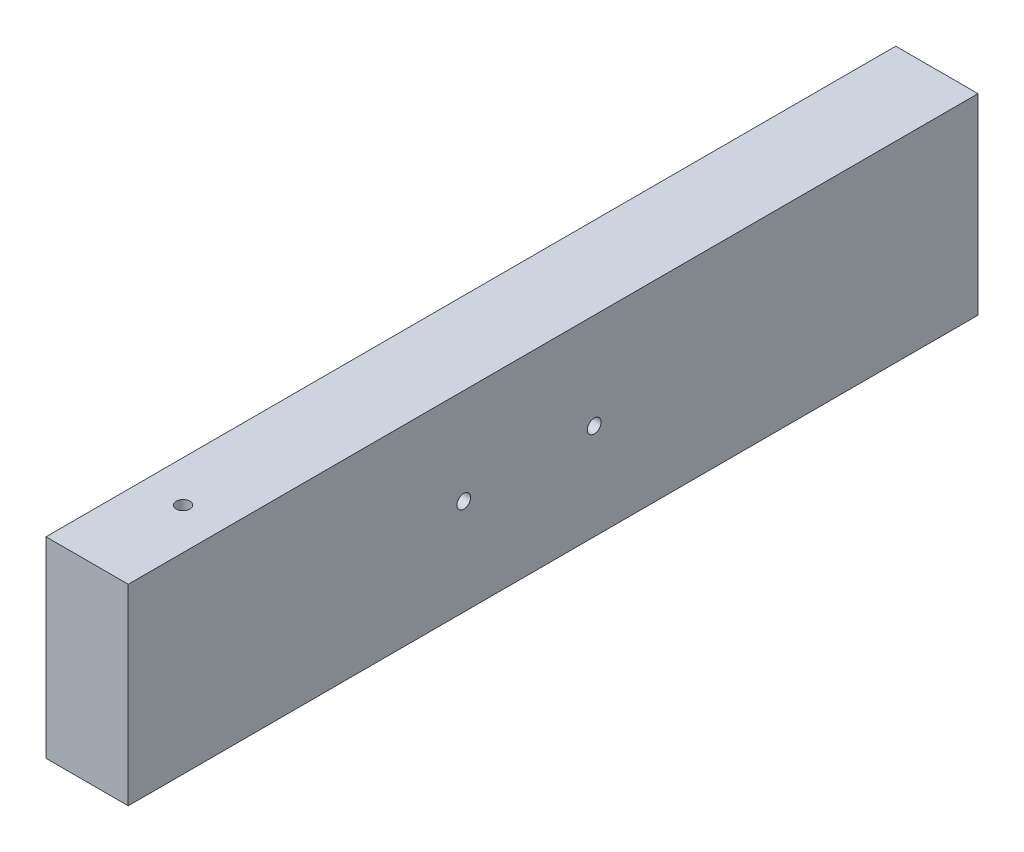
SolidWorks part; units mm, degrees
material "1060 Alloy"
ref_plane "Front Plane" through (0, 0, 0) normal (0, 0, 1) x (1, 0, 0)
ref_plane "Top Plane" through (0, 0, 0) normal (0, 1, 0) x (1, 0, 0)
ref_plane "Right Plane" through (0, 0, 0) normal (1, 0, 0) x (0, 0, -1)
sketch "Sketch1" plane through (0, 0, 0) normal (0, 1, 0) x (1, 0, 0)
  line L1 (-144.8803, -70.9153) -> (-106.7803, -70.9153)
  line L2 (-144.8803, -70.9153) -> (-144.8803, 322.7847)
  line L3 (-144.8803, 322.7847) -> (-106.7803, 322.7847)
  line L4 (-106.7803, -70.9153) -> (-106.7803, 322.7847)
  line L5 (-144.8803, -70.9153) -> (-106.7803, 322.7847) construction
  line L6 (-144.8803, 322.7847) -> (-106.7803, -70.9153) construction
  point P0 (-125.8303, 125.9347)
  dimension "D1" = 393.7
  dimension "D2" = 38.1
extrude "Boss-Extrude1" add sketch "Sketch1" along normal blind 88.9
sketch "Sketch2" plane through (0, 0, 0) normal (0, -1, 0) x (-1, 0, 0)
  line L0 (144.8803, -70.9153) -> (106.7803, -70.9153) construction
  line L1 (144.8803, 322.7847) -> (144.8803, -70.9153) construction
  circle A0 centre (125.8303, -26.4653) radius 3.175
  dimension "D1" = 6.35
  dimension "D2" = 44.45
  dimension "D3" = 19.05
sketch "Sketch3" plane through (-144.8803, 0, 0) normal (-1, 0, 0) x (0, 0, 1)
  line L0 (-322.7847, 88.9) -> (-322.7847, 0) construction
  line L1 (-322.7847, 88.9) -> (-322.7847, 0) construction
  line L2 (-322.7847, 0) -> (70.9153, 0) construction
  line L3 (70.9153, 88.9) -> (-322.7847, 88.9) construction
  circle A0 centre (-84.5327, 44.45) radius 3.175
  circle A1 centre (-144.9847, 44.45) radius 3.175
  dimension "D1" = 6.35
  dimension "D2" = 238.252
  dimension "D3" = 44.45
  dimension "D4" = 6.35
  dimension "D5" = 177.8
  dimension "D6" = 44.45
extrude "Cut-Extrude2" cut sketch "Sketch3" against normal through all
extrude "Cut-Extrude3" cut sketch "Sketch2" against normal through all
